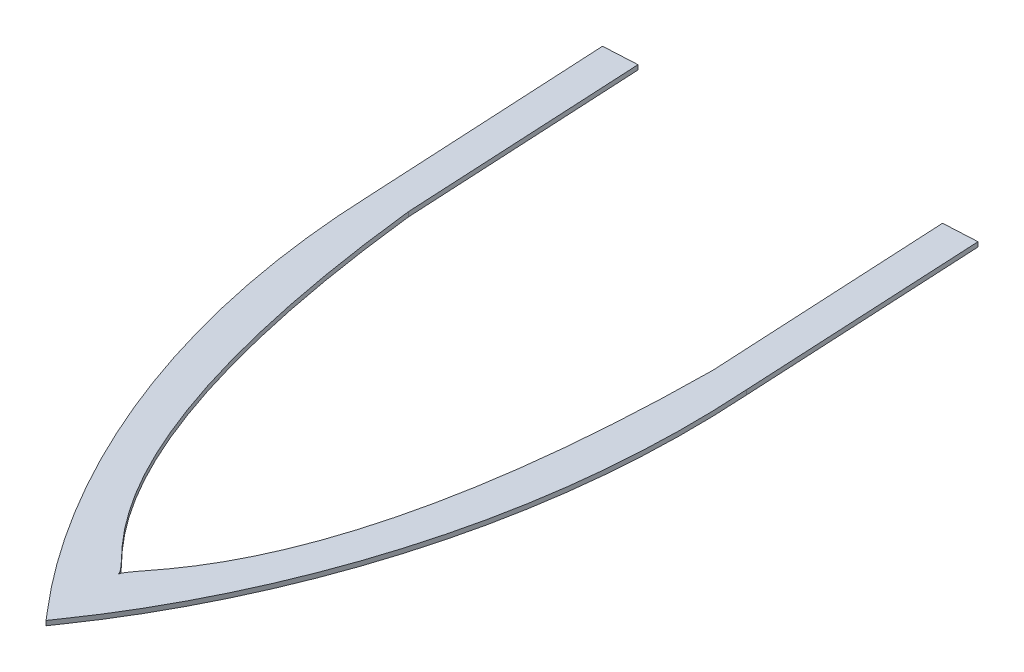
SolidWorks part; units mm, degrees
ref_plane "Front Plane" through (0, 0, 0) normal (0, 0, 1) x (1, 0, 0)
ref_plane "Top Plane" through (0, 0, 0) normal (0, 1, 0) x (1, 0, 0)
ref_plane "Right Plane" through (0, 0, 0) normal (1, 0, 0) x (0, 0, -1)
sketch "Sketch1" plane through (0, 0, 0) normal (0, 1, 0) x (1, 0, 0)
  line L0 (22.3021, 323.8571) -> (33.078, 112.2247)
  line L1 (-100.871, -299.2435) -> (-97.4553, -365.3593)
  line L2 (22.3021, 323.8571) -> (-6.9622, 322.3453)
  line L3 (-6.9622, 322.3453) -> (3.896, 112.1714)
  line L5 (-258.3352, 309.3586) -> (-247.477, 99.1847)
  line L6 (-287.5995, 307.8467) -> (-258.3352, 309.3586)
  line L7 (-287.5995, 307.8467) -> (-276.5092, 96.2305)
  spline S0 degree 3 poles (33.078, 112.2247) (51.9753, -177.0207) (-95.3135, -359.8399) (-97.4553, -365.3593) knots 0 0 0 0 1 1 1 1
  spline S1 degree 3 poles (3.896, 112.1714) (0.7923, -222.8045) (-99.7754, -283.2136) (-100.871, -299.2435) knots 0 0 0 0 1 1 1 1
  spline S2 degree 3 poles (-247.477, 99.1847) (-209.8702, -233.688) (-103.6127, -283.4119) (-100.871, -299.2435) knots 0 0 0 0 1 1 1 1
  spline S3 degree 3 poles (-276.5092, 96.2305) (-265.4988, -193.4224) (-100.1545, -360.09) (-97.4553, -365.3593) knots 0 0 0 0 1 1 1 1
extrude "Boss-Extrude1" add sketch "Sketch1" along normal blind 4 contours L7 S3 L1 S2 L5 L6 | L3 S1 L1 S0 L0 L2
ref_plane "Plane1" through (-116.0212, 0, 5.994) normal (0.9987, 0, -0.0516) x (-0.0516, 0, -0.9987)
